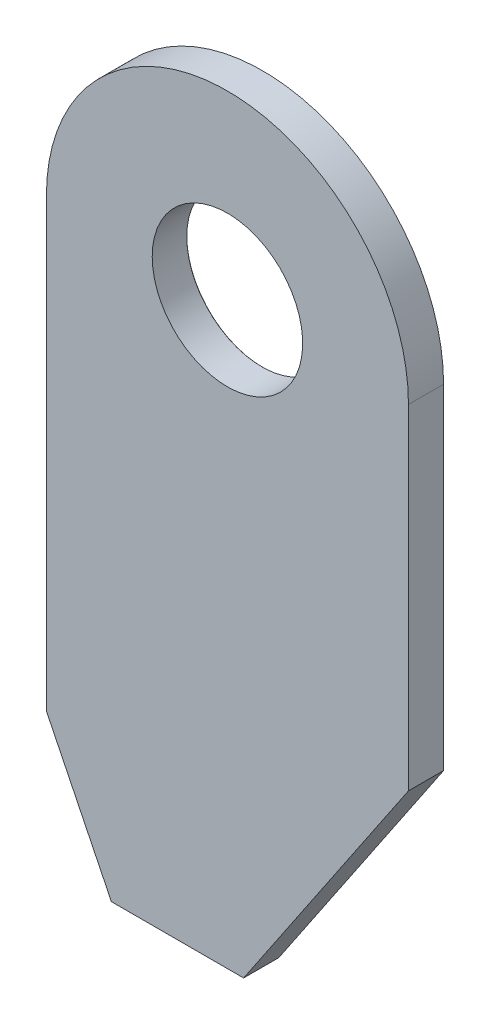
SolidWorks part; units mm, degrees
material "Alloy Steel"
ref_plane "Front Plane" through (0, 0, 0) normal (0, 0, 1) x (1, 0, 0)
ref_plane "Top Plane" through (0, 0, 0) normal (0, 1, 0) x (1, 0, 0)
ref_plane "Right Plane" through (0, 0, 0) normal (1, 0, 0) x (0, 0, -1)
sketch "Sketch1" plane through (0, 0, 0) normal (0, 0, 1) x (1, 0, 0)
  line L0 (-7.94, 0) -> (-7.94, -25.4)
  line L1 (-7.94, -25.4) -> (7.94, -25.4)
  line L2 (7.94, -25.4) -> (7.94, 0)
  line L3 (7.94, -14.6769) -> (0.7095, -25.4)
  line L4 (-5.0904, -25.4) -> (-7.94, -19.5835)
  circle A0 centre (0, 0) radius 7.94
  point P11 (-7.94, -17.4968)
  point P12 (7.94, -17.9769)
  point P13 (2.0971, -25.4)
  point P14 (7.94, -15.3537)
  point P15 (1.5366, -25.4)
  point P16 (0.7095, -25.4)
  point P17 (7.94, -14.6769)
  dimension "D1" = 15.88
  dimension "D2" = 25.4
extrude "Boss-Extrude1" add sketch "Sketch1" along normal blind 1.54 contours A0 L0 L1 L2
sketch "Sketch4" plane through (0, 0, 0) normal (0, 0, -1) x (-1, 0, 0)
  point P0 (0, 0)
hole_wizard "M6 Clearance Hole1" positions "Sketch4" profile "Sketch3" hole size "M6" standard "ANSI Metric" end condition through all
sketch "Sketch3" plane through (0, 0, 0) normal (1, 0, 0) x (0, 1, 0)
  line L0 (0, 0) -> (0, 1.54)
  line L1 (0, 1.54) -> (3.3, 1.54)
  line L2 (3.3, 1.54) -> (3.3, 0.025)
  line L3 (3.3, 0.025) -> (3.325, 0)
  line L5 (3.325, 0) -> (0, 0)
  line L6 (-3.3, 0.025) -> (-3.325, 0) construction
  line L11 (0, -6.35) -> (0, 107.95) construction
  dimension "Thru Hole Dia." = 6.6
  dimension "Thru Hole Depth" = 1.54
  dimension "Near C'Sink Dia." = 6.65
  dimension "Near C'Sink Angle" = 90
